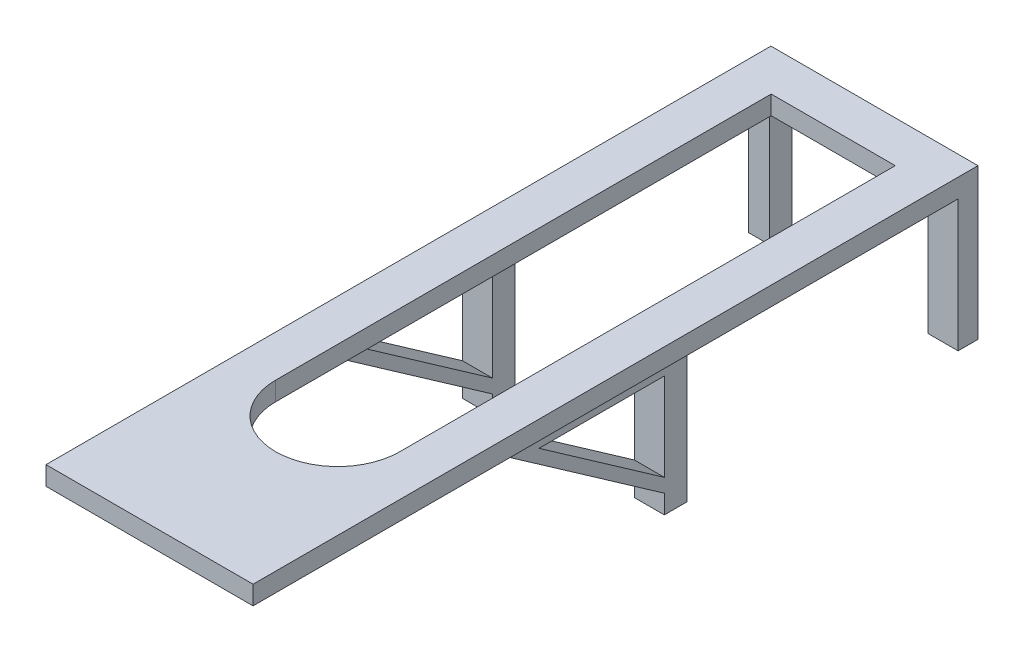
SolidWorks part; units mm, degrees
ref_plane "Plan de face" through (0, 0, 0) normal (0, 0, 1) x (1, 0, 0)
ref_plane "Plan de dessus" through (0, 0, 0) normal (0, 1, 0) x (1, 0, 0)
ref_plane "Plan de droite" through (0, 0, 0) normal (1, 0, 0) x (0, 0, -1)
sketch "Esquisse2" plane through (0, 0, 0) normal (0, 1, 0) x (1, 0, 0)
  line L0 (63.173, 102.455) -> (55.173, 102.455)
  line L1 (13.713, 101.825) -> (8.113, 101.825)
  line L2 (13.713, 101.825) -> (13.713, 107.755)
  line L3 (13.713, 107.755) -> (8.113, 107.755)
  line L4 (8.113, 101.825) -> (8.113, 107.755)
  line L5 (13.713, 101.825) -> (8.113, 107.755) construction
  line L6 (13.713, 107.755) -> (8.113, 101.825) construction
  line L7 (63.173, 102.455) -> (63.173, 107.755)
  line L8 (63.173, 107.755) -> (55.173, 107.755)
  line L9 (55.173, 102.455) -> (55.173, 107.755)
  line L10 (16.183, 25.625) -> (8.183, 25.625)
  line L11 (16.183, 25.625) -> (16.183, 31.625)
  line L12 (16.183, 31.625) -> (8.183, 31.625)
  line L13 (8.183, 25.625) -> (8.183, 31.625)
  line L14 (61.903, 25.625) -> (53.903, 25.625)
  line L15 (61.903, 25.625) -> (61.903, 31.625)
  line L16 (61.903, 31.625) -> (53.903, 31.625)
  line L17 (53.903, 25.625) -> (53.903, 31.625)
  circle A0 centre (12.183, 29.625) radius 1.6 construction
  circle A1 centre (57.903, 29.625) radius 1.6 construction
  circle A2 centre (10.913, 105.825) radius 1.6 construction
  circle A3 centre (59.173, 104.555) radius 1.6 construction
  point P8 (10.913, 104.79)
  dimension "D1" = 3.2
  dimension "D2" = 3.2
  dimension "D3" = 3.2
  dimension "D4" = 3.2
  dimension "D5" = 12.183
  dimension "D6" = 29.625
  dimension "D7" = 57.903
  dimension "D8" = 29.625
  dimension "D9" = 10.913
  dimension "D10" = 105.825
  dimension "D11" = 59.173
  dimension "D12" = 104.555
  dimension "D14" = 4
  dimension "D15" = 2.8
  dimension "D16" = 2.8
  dimension "D17" = 2.1
  dimension "D18" = 3.2
  dimension "D19" = 4
  dimension "D20" = 4
  dimension "D21" = 4
  dimension "D22" = 2
  dimension "D23" = 4
  dimension "D24" = 4
  dimension "D25" = 8
  dimension "D26" = 4
  dimension "D27" = 2
  dimension "D28" = 4
extrude "Boss.-Extru.1" add sketch "Esquisse2" along normal blind 35
ref_plane "Plan1" through (0, 35, 0) normal (0, 1, 0) x (1, 0, 0)
sketch "Esquisse3" plane through (0, 35, 0) normal (0, 1, 0) x (1, 0, 0)
  line L0 (13.713, 107.755) -> (8.113, 107.755) construction
  line L1 (63.173, -85) -> (8.113, -85)
  line L2 (63.173, -85) -> (63.173, 107.755)
  line L3 (63.173, 107.755) -> (8.113, 107.755)
  line L4 (8.113, -85) -> (8.113, 107.755)
  line L5 (63.173, -85) -> (8.113, 107.755) construction
  line L6 (63.173, 107.755) -> (8.113, -85) construction
  line L7 (8.113, 107.755) -> (8.113, 101.825) construction
  line L8 (63.173, 102.455) -> (63.173, 107.755) construction
  point P0 (35.643, 11.3775)
  dimension "D1" = 0
  dimension "D2" = 0
  dimension "D3" = 0
  dimension "D4" = 85
extrude "Boss.-Extru.2" add sketch "Esquisse3" along normal blind 5
ref_plane "Plan2" through (0, 0, -107.755) normal (0, 0, -1) x (-1, 0, 0)
sketch "Esquisse8" plane through (0, 35, 0) normal (0, 1, 0) x (1, 0, 0)
  line L0 (8.113, -85) -> (63.173, -85) construction
  line L1 (54.673, -84) -> (55.173, -84)
  line L2 (54.673, -84) -> (54.673, -59)
  line L3 (54.673, -59) -> (55.173, -59)
  line L4 (55.173, -84) -> (55.173, -59)
  line L5 (54.673, -84) -> (55.173, -59) construction
  line L6 (54.673, -59) -> (55.173, -84) construction
  line L7 (60.173, -84) -> (60.673, -84)
  line L8 (60.173, -84) -> (60.173, -59)
  line L9 (60.173, -59) -> (60.673, -59)
  line L10 (60.673, -84) -> (60.673, -59)
  line L11 (60.173, -84) -> (60.673, -59) construction
  line L12 (60.173, -59) -> (60.673, -84) construction
  line L26 (63.173, -85) -> (63.173, 102.455) construction
  line L27 (49.173, -84) -> (49.673, -84)
  line L28 (49.173, -84) -> (49.173, -59)
  line L29 (49.173, -59) -> (49.673, -59)
  line L30 (49.673, -84) -> (49.673, -59)
  line L31 (49.173, -84) -> (49.673, -59) construction
  line L32 (49.173, -59) -> (49.673, -84) construction
  line L33 (43.673, -84) -> (44.173, -84)
  line L34 (43.673, -84) -> (43.673, -59)
  line L35 (43.673, -59) -> (44.173, -59)
  line L36 (44.173, -84) -> (44.173, -59)
  line L37 (43.673, -84) -> (44.173, -59) construction
  line L38 (43.673, -59) -> (44.173, -84) construction
  line L39 (38.173, -84) -> (38.673, -84)
  line L40 (38.173, -84) -> (38.173, -59)
  line L41 (38.173, -59) -> (38.673, -59)
  line L42 (38.673, -84) -> (38.673, -59)
  line L43 (38.173, -84) -> (38.673, -59) construction
  line L44 (38.173, -59) -> (38.673, -84) construction
  line L45 (32.673, -84) -> (33.173, -84)
  line L46 (32.673, -84) -> (32.673, -59)
  line L47 (32.673, -59) -> (33.173, -59)
  line L48 (33.173, -84) -> (33.173, -59)
  line L49 (32.673, -84) -> (33.173, -59) construction
  line L50 (32.673, -59) -> (33.173, -84) construction
  line L51 (27.173, -84) -> (27.673, -84)
  line L52 (27.173, -84) -> (27.173, -59)
  line L53 (27.173, -59) -> (27.673, -59)
  line L54 (27.673, -84) -> (27.673, -59)
  line L55 (27.173, -84) -> (27.673, -59) construction
  line L56 (27.173, -59) -> (27.673, -84) construction
  line L57 (21.673, -84) -> (22.173, -84)
  line L58 (21.673, -84) -> (21.673, -59)
  line L59 (21.673, -59) -> (22.173, -59)
  line L60 (22.173, -84) -> (22.173, -59)
  line L61 (21.673, -84) -> (22.173, -59) construction
  line L62 (21.673, -59) -> (22.173, -84) construction
  line L63 (16.173, -84) -> (16.673, -84)
  line L64 (16.173, -84) -> (16.173, -59)
  line L65 (16.173, -59) -> (16.673, -59)
  line L66 (16.673, -84) -> (16.673, -59)
  line L67 (16.173, -84) -> (16.673, -59) construction
  line L68 (16.173, -59) -> (16.673, -84) construction
  line L69 (10.673, -84) -> (11.173, -84)
  line L70 (10.673, -84) -> (10.673, -59)
  line L71 (10.673, -59) -> (11.173, -59)
  line L72 (11.173, -84) -> (11.173, -59)
  line L73 (10.673, -84) -> (11.173, -59) construction
  line L74 (10.673, -59) -> (11.173, -84) construction
  point P0 (54.923, -71.5)
  point P5 (60.423, -71.5)
  point P23 (49.423, -71.5)
  point P30 (43.923, -71.5)
  point P35 (38.423, -71.5)
  point P40 (32.923, -71.5)
  point P45 (27.423, -71.5)
  point P50 (21.923, -71.5)
  point P55 (16.423, -71.5)
  point P60 (10.923, -71.5)
  dimension "D1" = 0.5
  dimension "D2" = 0.5
  dimension "D5" = 25
  dimension "D6" = 25
  dimension "D9" = 1
  dimension "D10" = 1
  dimension "D11" = 5
  dimension "D12" = 2.5
  dimension "D13" = 9
  dimension "D16" = 5
extrude "Enlèv. mat.-Extru.3" cut sketch "Esquisse8" along normal blind 3.5
sketch "Esquisse9" plane through (0, 35, 0) normal (0, 1, 0) x (1, 0, 0)
  line L0 (63.173, -85) -> (63.173, 102.455) construction
  line L1 (37.173, -80) -> (62.173, -80)
  line L2 (37.173, -80) -> (37.173, -79.5)
  line L3 (37.173, -79.5) -> (62.173, -79.5)
  line L4 (62.173, -80) -> (62.173, -79.5)
  line L5 (37.173, -80) -> (62.173, -79.5) construction
  line L6 (37.173, -79.5) -> (62.173, -80) construction
  line L7 (8.113, -85) -> (63.173, -85) construction
  line L8 (9.113, -80) -> (34.113, -80)
  line L9 (9.113, -80) -> (9.113, -79.5)
  line L10 (9.113, -79.5) -> (34.113, -79.5)
  line L11 (34.113, -80) -> (34.113, -79.5)
  line L12 (9.113, -80) -> (34.113, -79.5) construction
  line L13 (9.113, -79.5) -> (34.113, -80) construction
  line L14 (8.113, 101.825) -> (8.113, -85) construction
  line L15 (37.173, -77) -> (62.173, -77)
  line L16 (37.173, -77) -> (37.173, -76.5)
  line L17 (37.173, -76.5) -> (62.173, -76.5)
  line L18 (62.173, -77) -> (62.173, -76.5)
  line L19 (9.113, -77) -> (34.113, -77)
  line L20 (9.113, -77) -> (9.113, -76.5)
  line L21 (9.113, -76.5) -> (34.113, -76.5)
  line L22 (34.113, -77) -> (34.113, -76.5)
  line L23 (37.173, -77) -> (62.173, -76.5) construction
  line L24 (37.173, -76.5) -> (62.173, -77) construction
  line L25 (9.113, -77) -> (34.113, -76.5) construction
  line L26 (9.113, -76.5) -> (34.113, -77) construction
  line L27 (37.173, -74) -> (62.173, -74)
  line L28 (37.173, -74) -> (37.173, -73.5)
  line L29 (37.173, -73.5) -> (62.173, -73.5)
  line L30 (62.173, -74) -> (62.173, -73.5)
  line L31 (9.113, -74) -> (34.113, -74)
  line L32 (9.113, -74) -> (9.113, -73.5)
  line L33 (9.113, -73.5) -> (34.113, -73.5)
  line L34 (34.113, -74) -> (34.113, -73.5)
  line L35 (37.173, -74) -> (62.173, -73.5) construction
  line L36 (37.173, -73.5) -> (62.173, -74) construction
  line L37 (9.113, -74) -> (34.113, -73.5) construction
  line L38 (9.113, -73.5) -> (34.113, -74) construction
  line L39 (37.173, -71) -> (62.173, -71)
  line L40 (37.173, -71) -> (37.173, -70.5)
  line L41 (37.173, -70.5) -> (62.173, -70.5)
  line L42 (62.173, -71) -> (62.173, -70.5)
  line L43 (9.113, -71) -> (34.113, -71)
  line L44 (9.113, -71) -> (9.113, -70.5)
  line L45 (9.113, -70.5) -> (34.113, -70.5)
  line L46 (34.113, -71) -> (34.113, -70.5)
  line L47 (37.173, -71) -> (62.173, -70.5) construction
  line L48 (37.173, -70.5) -> (62.173, -71) construction
  line L49 (9.113, -71) -> (34.113, -70.5) construction
  line L50 (9.113, -70.5) -> (34.113, -71) construction
  line L51 (37.173, -68) -> (62.173, -68)
  line L52 (37.173, -68) -> (37.173, -67.5)
  line L53 (37.173, -67.5) -> (62.173, -67.5)
  line L54 (62.173, -68) -> (62.173, -67.5)
  line L55 (9.113, -68) -> (34.113, -68)
  line L56 (9.113, -68) -> (9.113, -67.5)
  line L57 (9.113, -67.5) -> (34.113, -67.5)
  line L58 (34.113, -68) -> (34.113, -67.5)
  line L59 (37.173, -68) -> (62.173, -67.5) construction
  line L60 (37.173, -67.5) -> (62.173, -68) construction
  line L61 (9.113, -68) -> (34.113, -67.5) construction
  line L62 (9.113, -67.5) -> (34.113, -68) construction
  line L63 (37.173, -65) -> (62.173, -65)
  line L64 (37.173, -65) -> (37.173, -64.5)
  line L65 (37.173, -64.5) -> (62.173, -64.5)
  line L66 (62.173, -65) -> (62.173, -64.5)
  line L67 (9.113, -65) -> (34.113, -65)
  line L68 (9.113, -65) -> (9.113, -64.5)
  line L69 (9.113, -64.5) -> (34.113, -64.5)
  line L70 (34.113, -65) -> (34.113, -64.5)
  line L71 (37.173, -65) -> (62.173, -64.5) construction
  line L72 (37.173, -64.5) -> (62.173, -65) construction
  line L73 (9.113, -65) -> (34.113, -64.5) construction
  line L74 (9.113, -64.5) -> (34.113, -65) construction
  line L75 (37.173, -62) -> (62.173, -62)
  line L76 (37.173, -62) -> (37.173, -61.5)
  line L77 (37.173, -61.5) -> (62.173, -61.5)
  line L78 (62.173, -62) -> (62.173, -61.5)
  line L79 (9.113, -62) -> (34.113, -62)
  line L80 (9.113, -62) -> (9.113, -61.5)
  line L81 (9.113, -61.5) -> (34.113, -61.5)
  line L82 (34.113, -62) -> (34.113, -61.5)
  line L83 (37.173, -62) -> (62.173, -61.5) construction
  line L84 (37.173, -61.5) -> (62.173, -62) construction
  line L85 (9.113, -62) -> (34.113, -61.5) construction
  line L86 (9.113, -61.5) -> (34.113, -62) construction
  point P0 (49.673, -79.75)
  point P10 (21.613, -79.75)
  point P17 (49.673, -76.75)
  point P22 (21.613, -76.75)
  point P27 (49.673, -73.75)
  point P32 (21.613, -73.75)
  point P37 (49.673, -70.75)
  point P42 (21.613, -70.75)
  point P47 (49.673, -67.75)
  point P52 (21.613, -67.75)
  point P57 (49.673, -64.75)
  point P62 (21.613, -64.75)
  point P67 (49.673, -61.75)
  point P72 (21.613, -61.75)
  dimension "D1" = 1
  dimension "D2" = 0.5
  dimension "D3" = 5
  dimension "D4" = 25
  dimension "D6" = 1
  dimension "D7" = 25
  dimension "D9" = 2.5
  dimension "D5" = 2
  dimension "D8" = 7
extrude "Enlèv. mat.-Extru.4" cut sketch "Esquisse9" along normal blind 3.5
ref_plane "Plan5" through (61.903, 0, 0) normal (1, 0, 0) x (0, 0, -1)
ref_plane "Plan6" through (8.183, 0, 0) normal (-1, 0, 0) x (0, 0, 1)
sketch "Esquisse13" plane through (61.903, 0, 0) normal (1, 0, 0) x (0, 0, -1)
  line L0 (25.625, 5) -> (-17.2194, 35)
  line L1 (25.625, 35) -> (25.625, 0) construction
  line L2 (77.2769, 35) -> (-77.2769, 35) construction
  line L3 (-17.2194, 35) -> (25.625, 35)
  line L4 (25.625, 35) -> (25.625, 5)
  line L5 (25.625, 0) -> (31.625, 0) construction
  dimension "D1" = 55
  dimension "D2" = 5
extrude "Boss.-Extru.3" add sketch "Esquisse13" against normal blind 8
sketch "Esquisse14" plane through (8.183, 0, 0) normal (-1, 0, 0) x (0, 0, 1)
  line L0 (-25.625, 5) -> (17.2194, 35)
  line L1 (77.2769, 35) -> (-77.2769, 35) construction
  line L2 (-101.825, 35) -> (85, 35) construction
  line L3 (17.2194, 35) -> (-25.625, 35)
  line L4 (-25.625, 35) -> (-25.625, 0) construction
  line L5 (-25.625, 35) -> (-25.625, 5)
  dimension "D1" = 55
extrude "Boss.-Extru.4" add sketch "Esquisse14" against normal blind 8
ref_plane "Plan7" through (0, 0, 0) normal (0, -1, 0) x (-1, 0, 0)
sketch "Esquisse15" plane through (0, 0, 0) normal (0, -1, 0) x (-1, 0, 0)
  circle A0 centre (-12.183, 29.625) radius 1.6
  circle A1 centre (-57.903, 29.625) radius 1.6
  circle A2 centre (-10.913, 105.825) radius 1.6
  circle A3 centre (-59.173, 104.555) radius 1.6
  dimension "D2" = 3.2
  dimension "D3" = 3.2
  dimension "D4" = 3.2
  dimension "D5" = 3.2
  dimension "D1" = 12.183
  dimension "D6" = 29.625
  dimension "D7" = 29.625
  dimension "D8" = 57.903
  dimension "D9" = 105.825
  dimension "D10" = 10.913
  dimension "D11" = 104.555
  dimension "D12" = 59.173
extrude "Enlèv. mat.-Extru.5" cut sketch "Esquisse15" against normal blind 15
sketch "Esquisse16" plane through (8.113, 0, 0) normal (-1, 0, 0) x (0, 0, 1)
  line L2 (-35.6275, 0) -> (35.6275, 0) construction
  circle A0 centre (-105.825, 12) radius 1
  dimension "D3" = 2
  dimension "D1" = 105.825
  dimension "D4" = 12
extrude "Enlèv. mat.-Extru.6" [suppressed] cut sketch "Esquisse16" against normal blind 9.6
sketch "Esquisse18" plane through (63.173, 0, 0) normal (1, 0, 0) x (0, 0, -1)
  line L0 (-35.6275, 0) -> (35.6275, 0) construction
  circle A0 centre (104.555, 12) radius 1
  dimension "D2" = 2
  dimension "D1" = 12
  dimension "D3" = 104.555
extrude "Enlèv. mat.-Extru.7" [suppressed] cut sketch "Esquisse18" against normal blind 9.6
sketch "Esquisse19" plane through (8.183, 0, 0) normal (-1, 0, 0) x (0, 0, 1)
  line L2 (-25.625, 8.6623) -> (7.7047, 32)
  line L3 (7.7047, 32) -> (-25.625, 32)
  line L4 (-25.625, 32) -> (-25.625, 8.6623)
  line L5 (-25.625, 5) -> (-25.625, 0) construction
  line L6 (-101.825, 35) -> (85, 35) construction
  line L7 (-25.625, 5) -> (17.2194, 35) construction
  dimension "D4" = 0
  dimension "D5" = 3
  dimension "D7" = 3
extrude "Enlèv. mat.-Extru.8" cut sketch "Esquisse19" against normal through all
sketch "Esquisse20" plane through (0, 40, 0) normal (0, 1, 0) x (1, 0, 0)
  line L0 (44.712, 107.755) -> (-44.712, 107.755) construction
  line L1 (19.183, 96.755) -> (52.173, 96.755)
  line L2 (19.183, 96.755) -> (19.183, -35)
  line L4 (52.173, 96.755) -> (52.173, -35)
  line L5 (8.113, -85) -> (63.173, -85) construction
  line L7 (8.183, 110.1157) -> (8.183, -110.1157) construction
  line L8 (63.173, -85) -> (63.173, 107.755) construction
  arc A0 (19.183, -35) -> (52.173, -35) centre (35.678, -35) ccw
  point P0 (35.678, 39.7678)
  point P11 (19.183, -17.2194)
  dimension "D4" = 50
  dimension "D1" = 11
  dimension "D2" = 11
  dimension "D3" = 11
extrude "Enlèv. mat.-Extru.9" cut sketch "Esquisse20" against normal up to next
